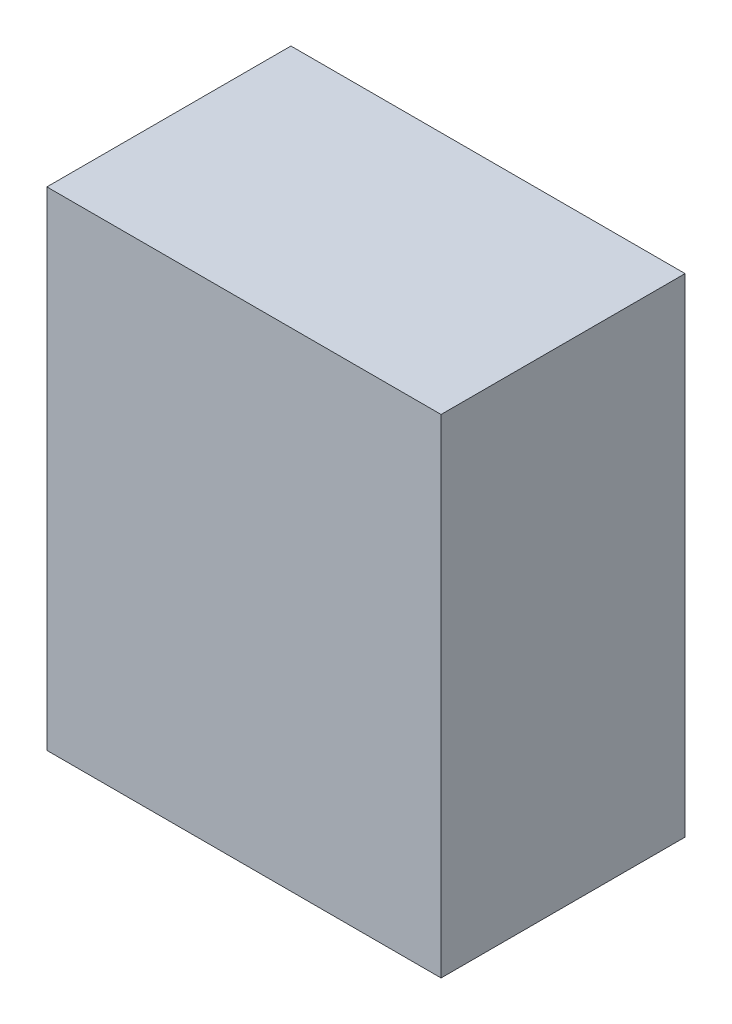
SolidWorks part; units mm, degrees
material "Material"
ref_plane "Front Plane" through (0, 0, 0) normal (0, 0, 1) x (1, 0, 0)
ref_plane "Top Plane" through (0, 0, 0) normal (0, 1, 0) x (1, 0, 0)
ref_plane "Right Plane" through (0, 0, 0) normal (1, 0, 0) x (0, 0, -1)
ref_plane "Plane1" through (0, 0, 0) normal (0, 0, -1) x (-1, 0, 0)
sketch "Sketch1" plane through (0, 0, 0) normal (0, 0, -1) x (-1, 0, 0)
  line L0 (0, 0) -> (-42, 0)
  line L1 (-42, 0) -> (-42, -52)
  line L2 (-42, -52) -> (0, -52)
  line L3 (0, -52) -> (0, 0)
extrude "Boss-Extrude1" add sketch "Sketch1" against normal blind 26
